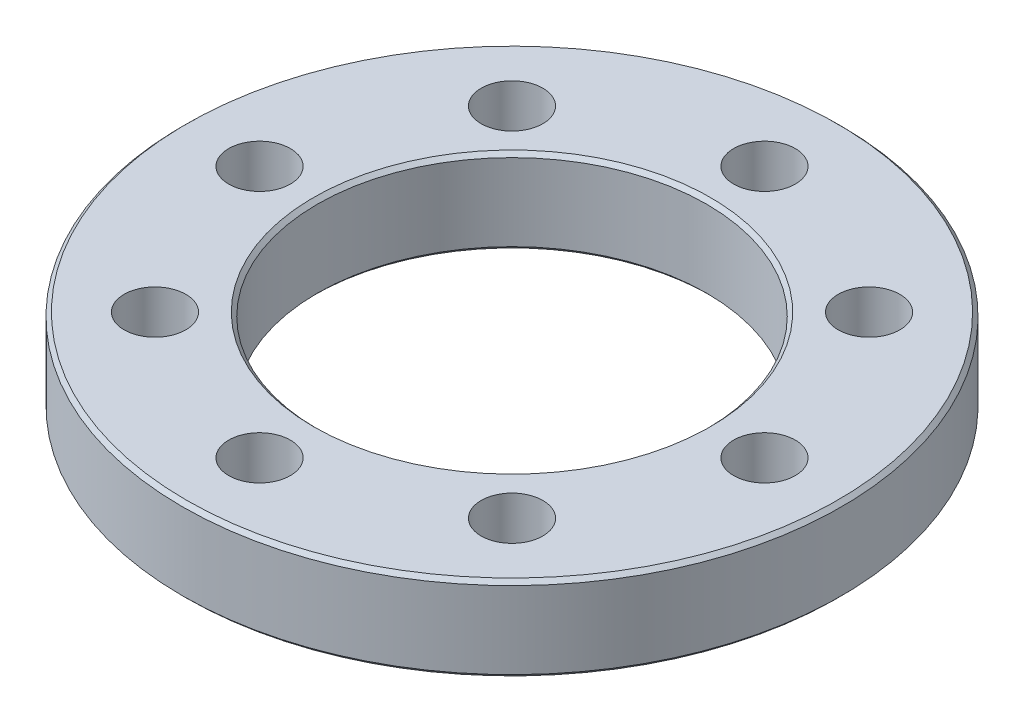
SolidWorks part; units mm, degrees
ref_plane "前视基准面" through (0, 0, 0) normal (0, 0, 1) x (1, 0, 0)
ref_plane "上视基准面" through (0, 0, 0) normal (0, 1, 0) x (1, 0, 0)
ref_plane "右视基准面" through (0, 0, 0) normal (1, 0, 0) x (0, 0, -1)
sketch "草图1" plane through (0, 0, 0) normal (0, 1, 0) x (1, 0, 0)
  circle A0 centre (0, 0) radius 85.5
  circle A1 centre (0, 0) radius 50.5
  dimension "D1" = 171
  dimension "D2" = 101
extrude "凸台-拉伸1" add sketch "草图1" along normal blind 22
chamfer "倒角1" distance 1 angle 45 4 edges at (0, 0, 85.5) (0, 22, 85.5) (0, 0, 50.5) (0, 22, 50.5)
sketch "草图2" plane through (0, 22, 0) normal (0, 1, 0) x (1, 0, 0)
  circle A0 centre (0, 0) radius 65.5 construction
  point P3 (65.5, 0)
  point P6 (46.3155, -46.3155)
  point P7 (0, -65.5)
  point P8 (-46.3155, -46.3155)
  point P9 (-65.5, 0)
  point P10 (-46.3155, 46.3155)
  point P11 (0, 65.5)
  point P12 (46.3155, 46.3155)
  dimension "D1" = 131
  dimension "D2" = 8
hole_wizard "孔1" positions "草图2" profile "草图3" legacy end condition up to next
sketch "草图3" plane through (46.3155, 22, -46.3155) normal (1, 0, 0) x (0, 0, 1)
  line L0 (0, 0) -> (0, 22)
  line L1 (0, 22) -> (8, 22)
  line L2 (8, 22) -> (8, 0)
  line L3 (8, 0) -> (0, 0)
  line L4 (0, 110) -> (0, -10) construction
  dimension "直径" = 16
  dimension "深度" = 22
